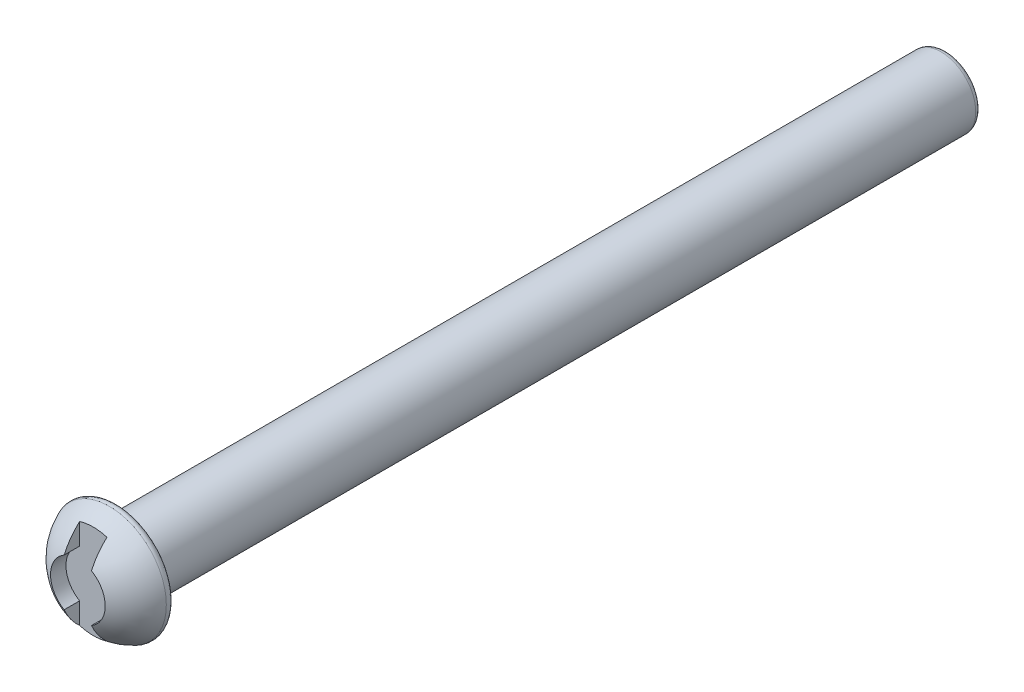
SolidWorks part; units mm, degrees
ref_plane "Front Plane" through (0, 0, 0) normal (0, 0, 1) x (1, 0, 0)
ref_plane "Top Plane" through (0, 0, 0) normal (0, 1, 0) x (1, 0, 0)
ref_plane "Right Plane" through (0, 0, 0) normal (1, 0, 0) x (0, 0, -1)
sketch "Sketch4" plane through (0, 0, 0) normal (1, 0, 0) x (0, 0, -1)
  line L0 (0, 0) -> (24, 0)
  line L1 (24, 0) -> (24, 0.95)
  line L2 (24, 0.95) -> (1.25, 0.95)
  line L3 (1.25, 1.63) -> (1.25, 0.95)
  arc A0 (1.25, 1.63) -> (0, 0) centre (1.6878, 0) ccw
  dimension "D1" = 24
  dimension "D2" = 0.95
  dimension "D3" = 1.63
  dimension "D4" = 1.25
revolve "Revolve2" add sketch "Sketch4" angle 360 about L0
sketch "Sketch5" plane through (0, 0, 0) normal (0, 0, 1) x (1, 0, 0)
  line L0 (-0.375, -0.6495) -> (-0.375, -1.871)
  line L1 (0.375, 1.871) -> (-0.375, 1.871)
  line L2 (0.375, 1.871) -> (0.375, 0.6495)
  line L3 (0.375, -1.871) -> (-0.375, -1.871)
  line L4 (-0.375, 1.871) -> (-0.375, 0.6495)
  line L9 (0.375, -0.6495) -> (0.375, -1.871)
  arc A0 (-0.375, 0.6495) -> (-0.375, -0.6495) centre (0, 0) ccw
  arc A1 (0.375, -0.6495) -> (0.375, 0.6495) centre (0, 0) ccw
  point P0 (0, 0)
  dimension "D2" = 1.5
  dimension "D1" = 0.75
extrude "Cut-Extrude1" cut sketch "Sketch5" against normal blind 0.6
fillet "Fillet1" radius 0.15 2 edges at (1.63, 0, -1.25) (0.95, 0, -24)
